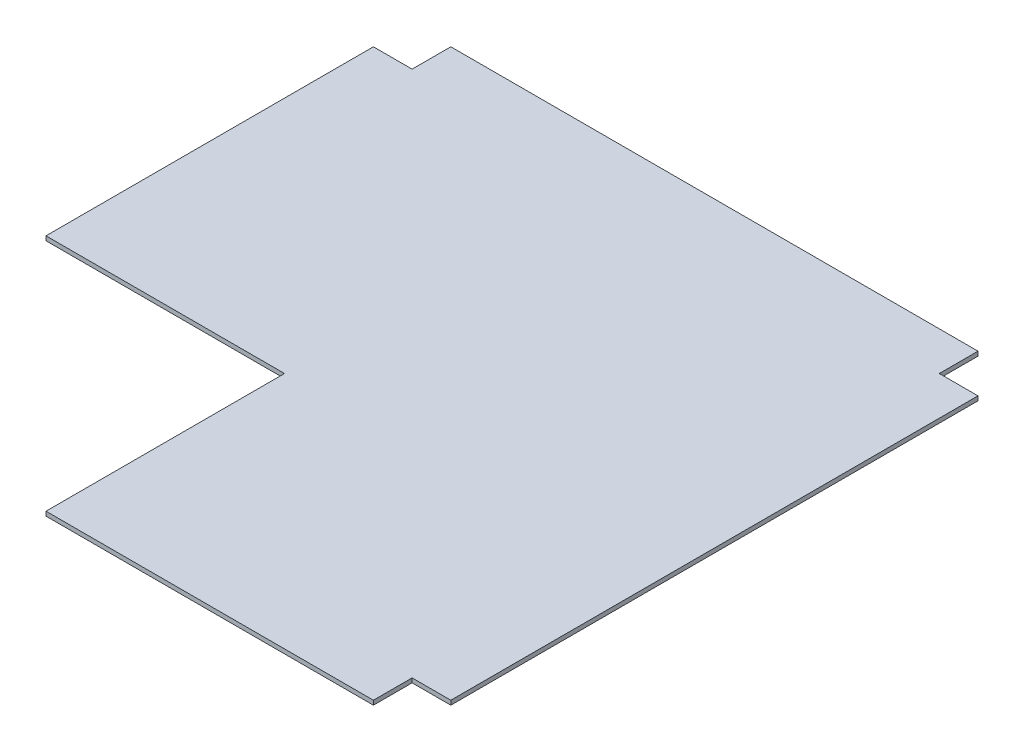
SolidWorks part; units mm, degrees
ref_plane "Front Plane" through (0, 0, 0) normal (0, 0, 1) x (1, 0, 0)
ref_plane "Top Plane" through (0, 0, 0) normal (0, 1, 0) x (1, 0, 0)
ref_plane "Right Plane" through (0, 0, 0) normal (1, 0, 0) x (0, 0, -1)
sketch "Sketch1" plane through (0, 0, 0) normal (0, 1, 0) x (1, 0, 0)
  line L1 (0, 0) -> (443.65, 0)
  line L2 (0, 0) -> (0, 443.65)
  line L3 (0, 443.65) -> (443.65, 443.65)
  line L4 (443.65, 0) -> (443.65, 443.65)
  line L5 (0, 0) -> (28.4, 0)
  line L6 (0, 0) -> (0, 28.4)
  line L7 (0, 28.4) -> (28.4, 28.4)
  line L8 (28.4, 0) -> (28.4, 28.4)
  line L9 (0, 443.65) -> (28.4, 443.65)
  line L10 (0, 443.65) -> (0, 415.25)
  line L11 (0, 415.25) -> (28.4, 415.25)
  line L12 (28.4, 443.65) -> (28.4, 415.25)
  line L13 (443.65, 443.65) -> (415.25, 443.65)
  line L14 (443.65, 443.65) -> (443.65, 415.25)
  line L15 (443.65, 415.25) -> (415.25, 415.25)
  line L16 (415.25, 443.65) -> (415.25, 415.25)
  line L17 (443.65, 0) -> (415.25, 0)
  line L18 (443.65, 0) -> (443.65, 28.4)
  line L19 (443.65, 28.4) -> (415.25, 28.4)
  line L20 (415.25, 0) -> (415.25, 28.4)
  line L21 (0, 0) -> (175, 0)
  line L22 (0, 0) -> (0, 175)
  line L23 (0, 175) -> (175, 175)
  line L24 (175, 0) -> (175, 175)
  dimension "D1" = 443.65
  dimension "D2" = 443.65
  dimension "D3" = 28.4
  dimension "D4" = 175
extrude "Boss-Extrude1" add sketch "Sketch1" along normal blind 3.175 contours L1 L20 L19 L4 L15 L16 L3 L12 L11 L2 L7 L8
